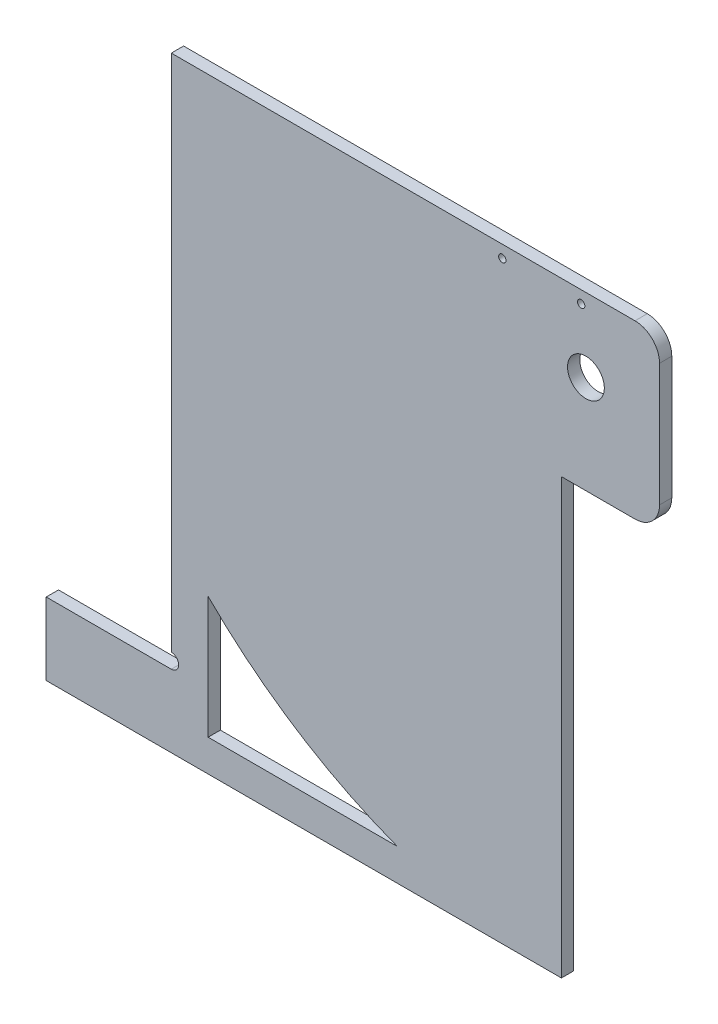
SolidWorks part; units mm, degrees
ref_plane "前视基准面" through (0, 0, 0) normal (0, 0, 1) x (1, 0, 0)
ref_plane "上视基准面" through (0, 0, 0) normal (0, 1, 0) x (1, 0, 0)
ref_plane "右视基准面" through (0, 0, 0) normal (1, 0, 0) x (0, 0, -1)
sketch "草图1" plane through (0, 0, 0) normal (0, 0, 1) x (1, 0, 0)
  line L0 (210, -237) -> (210, -247)
  line L1 (10, 0) -> (210, 0)
  line L2 (0, -10) -> (0, -237)
  line L3 (10, -247) -> (200, -247)
  line L4 (210, 0) -> (210, -237)
  line L5 (210, 0) -> (240, 0)
  line L6 (210, 0) -> (210, -70)
  line L7 (210, -70) -> (240, -70)
  line L8 (250, -10) -> (250, -60)
  line L9 (210, -247) -> (200, -247)
  line L10 (0, -237) -> (0, -247)
  line L11 (10, -247) -> (0, -247)
  arc A0 (240, 0) -> (250, -10) centre (240, -10) cw
  arc A1 (240, -70) -> (250, -60) centre (240, -60) ccw
  arc A4 (10, 0) -> (0, -10) centre (10, -10) ccw
  point P10 (250, 0)
  point P13 (250, -70)
  point P18 (0, -247)
  point P21 (0, 0)
  dimension "D5" = 10
  dimension "D1" = 247
  dimension "D2" = 210
  dimension "D3" = 40
  dimension "D4" = 70
extrude "凸台-拉伸1" add sketch "草图1" along normal blind 5 contours L3 L9 L0 L4 L1 A4 L2 L10 L11 | L6 L7 A1 L8 A0 L5
sketch "草图2" plane through (0, 0, 5) normal (0, 0, 1) x (1, 0, 0)
  line L0 (160.7676, 0) -> (160.7676, -30) construction
  line L1 (10, 0) -> (240, 0) construction
  line L2 (250, -30) -> (0, -30) construction
  line L3 (250, -10) -> (250, -60) construction
  line L4 (0, -10) -> (0, -247) construction
  line L5 (210, -70) -> (210, 0) construction
  line L6 (210, -30) -> (220, -30) construction
  circle A0 centre (220, -30) radius 7.5
  dimension "D3" = 15
  dimension "D1" = 30
  dimension "D2" = 10
extrude "切除-拉伸1" cut sketch "草图2" against normal blind 5
sketch "草图3" plane through (0, 0, 0) normal (-1, 0, 0) x (0, 0, 1)
  line L1 (0, -10) -> (0, -247) construction
  line L3 (5, -10) -> (5, -247) construction
  line L5 (5, -214.5) -> (6.3865, -214.5) construction
  line L16 (0, -217.5) -> (5, -217.5)
  line L19 (0, -217.5) -> (0, -211.5)
  line L20 (0, -211.5) -> (5, -211.5)
  line L21 (5, -217.5) -> (5, -211.5)
  point P15 (0, -214.5)
extrude "切除-拉伸3" cut sketch "草图3" against normal blind 51
sketch "草图4" plane through (0, 0, 5) normal (0, 0, 1) x (1, 0, 0)
  line L0 (51, -211.5) -> (51, -217.5) construction
  line L1 (51, -211.5) -> (51, -217.5)
  arc A0 (51, -217.5) -> (51, -211.5) centre (51, -214.5) ccw
extrude "切除-拉伸4" cut sketch "草图4" against normal up to next
sketch "草图6" plane through (0, 0, 5) normal (0, 0, 1) x (1, 0, 0)
  circle A0 centre (218.077, -5) radius 1.5 construction
  circle A1 centre (218.077, -5) radius 1.5
  circle A2 centre (185.9216, -5) radius 1.5 construction
  circle A3 centre (185.9216, -5) radius 1.5
extrude "切除-拉伸6" cut sketch "草图6" against normal up to next
sketch "草图7" plane through (0, 0, 5) normal (0, 0, 1) x (1, 0, 0)
  line L0 (10, 0) -> (240, 0) construction
  line L1 (0, -217.5) -> (51, -217.5)
  line L2 (0, -217.5) -> (0, 0)
  line L3 (0, 0) -> (51, 0)
  line L4 (51, -217.5) -> (51, 0)
extrude "切除-拉伸7" cut sketch "草图7" against normal up to next
sketch "草图8" plane through (0, 0, 0) normal (0, 0, -1) x (-1, 0, 0)
  line L0 (-62.701, -180.9338) -> (-66, -184.2984)
  line L1 (-66, -184.2984) -> (-66, -234)
  line L2 (-66, -234) -> (-143.1365, -234)
  line L3 (0, -247) -> (-210, -247) construction
  line L4 (-51, 0) -> (-51, -211.5) construction
  circle A0 centre (-220, -30) radius 215 construction
  circle A1 centre (-220, -30) radius 218
  dimension "D1" = 430
  dimension "D2" = 3
  dimension "D3" = 13
  dimension "D4" = 15
extrude "切除-拉伸9" cut sketch "草图8" against normal blind 10 contours A1 L2 L1
